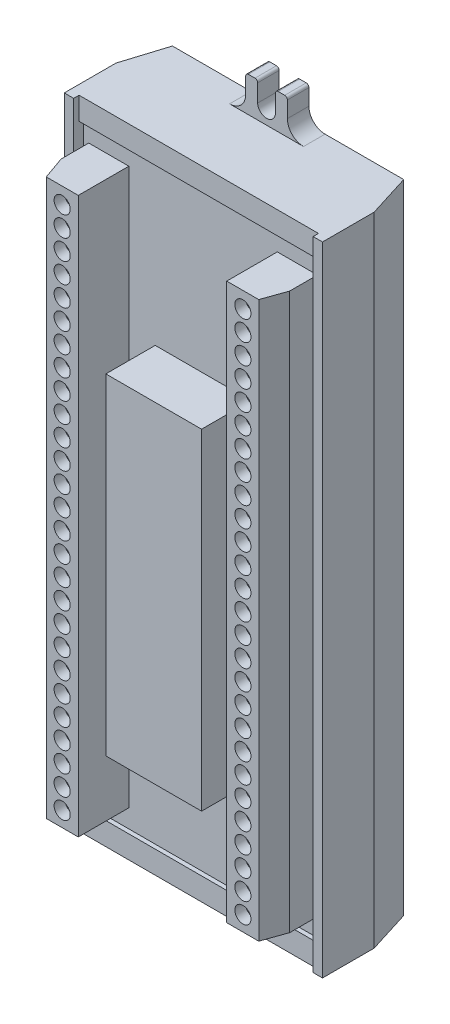
SolidWorks part; units mm, degrees
ref_plane "Front" through (0, 0, 0) normal (0, 0, 1) x (1, 0, 0)
ref_plane "Top" through (0, 0, 0) normal (0, 1, 0) x (1, 0, 0)
ref_plane "Right" through (0, 0, 0) normal (1, 0, 0) x (0, 0, -1)
sketch "Sketch1" plane through (0, 0, 0) normal (0, 1, 0) x (1, 0, 0)
  line L1 (-24, 8.8) -> (24, 8.8)
  line L2 (-24, 8.8) -> (-24, -8.8)
  line L3 (-24, -8.8) -> (24, -8.8)
  line L4 (24, 8.8) -> (24, -8.8)
  line L5 (-24, 8.8) -> (24, -8.8) construction
  line L6 (-24, -8.8) -> (24, 8.8) construction
  point P0 (0, 0)
  dimension "D1" = 48
  dimension "D2" = 17.6
extrude "Boss-Extrude1" add sketch "Sketch1" along normal blind 118.5
sketch "Sketch2" plane through (0, 0, 0) normal (0, -1, 0) x (1, 0, 0)
  line L0 (-24, 8.8) -> (24, 8.8) construction
  line L1 (-22.25, 8.8) -> (22.25, 8.8)
  line L2 (-22.25, 8.8) -> (-22.25, 7.8)
  line L3 (-22.25, 7.8) -> (22.25, 7.8)
  line L4 (22.25, 8.8) -> (22.25, 7.8)
  line L5 (-24, -8.8) -> (-24, 8.8) construction
  line L6 (24, 8.8) -> (24, -8.8) construction
  line L7 (-24, -0.8) -> (-21.5, -8.8)
  line L8 (24, -8.8) -> (-24, -8.8) construction
  line L9 (-21.5, -8.8) -> (-24, -8.8)
  line L10 (-24, -8.8) -> (-24, -0.8)
  line L11 (24, -8.8) -> (21.5, -8.8)
  line L12 (21.5, -8.8) -> (24, -0.8)
  line L13 (24, -0.8) -> (24, -8.8)
  dimension "D1" = 1
  dimension "D2" = 1.75
  dimension "D3" = 1.75
  dimension "D4" = 8
  dimension "D5" = 8
  dimension "D6" = 2.5
  dimension "D7" = 2.5
extrude "Cut-Extrude1" cut sketch "Sketch2" against normal through all
sketch "Sketch3" plane through (0, 0, 7.8) normal (0, 0, 1) x (1, 0, 0)
  line L0 (-22.25, 118.5) -> (-22.25, 0) construction
  line L1 (-22.25, 114.3) -> (22.25, 114.3)
  line L2 (-22.25, 114.3) -> (-22.25, 4.2)
  line L3 (-22.25, 4.2) -> (22.25, 4.2)
  line L4 (22.25, 114.3) -> (22.25, 4.2)
  line L5 (22.25, 118.5) -> (22.25, 0) construction
  line L6 (-22.25, 118.5) -> (22.25, 118.5) construction
  line L7 (-22.25, 0) -> (22.25, 0) construction
  dimension "D1" = 4.2
  dimension "D2" = 4.2
extrude "Cut-Extrude2" cut sketch "Sketch3" against normal blind 0.8
sketch "Sketch4" plane through (0, 0, -8.8) normal (0, 0, -1) x (-1, 0, 0)
  line L0 (0, 148.6078) -> (0, -24.1763) construction
  line L1 (-21.5, 118.5) -> (21.5, 118.5) construction
  line L2 (-3.875, 125) -> (3.875, 125)
  line L3 (-3.875, 125) -> (-3.875, 118.5)
  line L4 (-3.875, 118.5) -> (3.875, 118.5)
  line L5 (3.875, 125) -> (3.875, 118.5)
  line L6 (-3.875, 125) -> (3.875, 118.5) construction
  line L7 (-3.875, 118.5) -> (3.875, 125) construction
  line L8 (-21.5, 0) -> (21.5, 0) construction
  line L9 (3.875, -6.5) -> (-3.875, -6.5)
  line L10 (3.875, -6.5) -> (3.875, 0)
  line L11 (3.875, 0) -> (-3.875, 0)
  line L12 (-3.875, -6.5) -> (-3.875, 0)
  line L13 (3.875, -6.5) -> (-3.875, 0) construction
  line L14 (3.875, 0) -> (-3.875, -6.5) construction
  point P3 (0, 121.75)
  point P10 (0, -3.25)
  dimension "D1" = 6.5
  dimension "D2" = 6.5
  dimension "D3" = 7.75
  dimension "D4" = 7.75
extrude "Boss-Extrude2" add sketch "Sketch4" against normal blind 4
fillet "Fillet1" radius 3 4 edges at (-3.875, 118.5, -6.8) (3.875, 118.5, -6.8) (3.875, 0, -6.8) (-3.875, 0, -6.8)
sketch "Sketch5" plane through (0, 0, -8.8) normal (0, 0, -1) x (-1, 0, 0)
  line L0 (0, 132.5228) -> (0, -15.2026) construction
  line L1 (0, 129.8065) -> (0, 121.25) construction
  line L2 (1.65, 129.8065) -> (1.65, 121.25)
  line L3 (-1.65, 129.8065) -> (-1.65, 121.25)
  line L4 (0, -2.75) -> (0, -10.353) construction
  line L5 (1.65, -2.75) -> (1.65, -10.353)
  line L6 (-1.65, -2.75) -> (-1.65, -10.353)
  line L7 (-24, 59.25) -> (24, 59.25) construction
  line L8 (-24, 118.5) -> (-24, 0) construction
  line L9 (24, 118.5) -> (24, 0) construction
  arc A0 (1.65, 129.8065) -> (-1.65, 129.8065) centre (0, 129.8065) ccw
  arc A1 (-1.65, 121.25) -> (1.65, 121.25) centre (0, 121.25) ccw
  arc A2 (1.65, -2.75) -> (-1.65, -2.75) centre (0, -2.75) ccw
  arc A3 (-1.65, -10.353) -> (1.65, -10.353) centre (0, -10.353) ccw
  point P5 (0, 125.5283)
  point P10 (0, -6.5515)
  point P17 (1.65, 125.5283)
  dimension "D3" = 62
  dimension "D4" = 62
  dimension "D1" = 3.3
  dimension "D2" = 3.3
extrude "Cut-Extrude3" cut sketch "Sketch5" against normal through all
fillet "Fillet2" radius 0.5 8 edges at (3.875, -6.5, -6.8) (1.65, -6.5, -6.8) (-1.65, -6.5, -6.8) (-3.875, -6.5, -6.8) (-3.875, 125, -6.8) (-1.65, 125, -6.8) (1.65, 125, -6.8) (3.875, 125, -6.8)
sketch "Sketch6" plane through (0, 0, 7) normal (0, 0, 1) x (1, 0, 0)
  line L0 (22.25, 114.3) -> (-22.25, 114.3) construction
  line L1 (-21.25, 110.9) -> (-13.8, 110.9)
  line L2 (-21.25, 110.9) -> (-21.25, 7.6)
  line L3 (-21.25, 7.6) -> (-13.8, 7.6)
  line L4 (-13.8, 110.9) -> (-13.8, 7.6)
  line L5 (-22.25, 4.2) -> (22.25, 4.2) construction
  line L6 (-22.25, 114.3) -> (-22.25, 4.2) construction
  line L7 (0, 114.3) -> (0, 0) construction
  line L8 (13.8, 110.9) -> (13.8, 7.6)
  line L9 (21.25, 7.6) -> (13.8, 7.6)
  line L10 (21.25, 110.9) -> (21.25, 7.6)
  line L11 (21.25, 110.9) -> (13.8, 110.9)
  dimension "D1" = 103.3
  dimension "D2" = 7.45
  dimension "D3" = 3.4
  dimension "D4" = 3.4
  dimension "D5" = 1
extrude "Boss-Extrude3" add sketch "Sketch6" along normal blind 9.4
sketch "Sketch7" plane through (0, 7.6, 0) normal (0, -1, 0) x (1, 0, 0)
  line L0 (-19.75, 16.4) -> (-21.25, 12.15)
  line L1 (-21.25, 16.4) -> (-13.8, 16.4) construction
  line L2 (-21.25, 16.4) -> (-21.25, 7) construction
  line L3 (-21.25, 12.15) -> (-21.25, 16.4)
  line L4 (-21.25, 16.4) -> (-19.75, 16.4)
  line L5 (0, 0) -> (0, 20.5716) construction
  line L6 (21.25, 16.4) -> (19.75, 16.4)
  line L7 (21.25, 12.15) -> (21.25, 16.4)
  line L8 (19.75, 16.4) -> (21.25, 12.15)
  dimension "D1" = 4.25
  dimension "D2" = 1.5
extrude "Cut-Extrude4" cut sketch "Sketch7" against normal through all
sketch "Sketch8" plane through (0, 0, 16.4) normal (0, 0, 1) x (1, 0, 0)
  line L0 (-13.8, 7.6) -> (-13.8, 110.9) construction
  line L1 (-13.8, 110.9) -> (-21.25, 110.9) construction
  line L2 (0, 0) -> (0, 144.4934) construction
  circle A0 centre (-16.8, 107.9) radius 1.5
  circle A1 centre (-16.8, 104.15) radius 1.5
  circle A2 centre (-16.8, 100.4) radius 1.5
  circle A3 centre (-16.8, 96.65) radius 1.5
  circle A4 centre (-16.8, 92.9) radius 1.5
  circle A5 centre (-16.8, 89.15) radius 1.5
  circle A6 centre (-16.8, 85.4) radius 1.5
  circle A7 centre (-16.8, 81.65) radius 1.5
  circle A8 centre (-16.8, 77.9) radius 1.5
  circle A9 centre (-16.8, 74.15) radius 1.5
  circle A10 centre (-16.8, 70.4) radius 1.5
  circle A11 centre (-16.8, 66.65) radius 1.5
  circle A12 centre (-16.8, 62.9) radius 1.5
  circle A13 centre (-16.8, 59.15) radius 1.5
  circle A14 centre (-16.8, 55.4) radius 1.5
  circle A15 centre (-16.8, 51.65) radius 1.5
  circle A16 centre (-16.8, 47.9) radius 1.5
  circle A17 centre (-16.8, 44.15) radius 1.5
  circle A18 centre (-16.8, 40.4) radius 1.5
  circle A19 centre (-16.8, 36.65) radius 1.5
  circle A20 centre (-16.8, 32.9) radius 1.5
  circle A21 centre (-16.8, 29.15) radius 1.5
  circle A22 centre (-16.8, 25.4) radius 1.5
  circle A23 centre (-16.8, 21.65) radius 1.5
  circle A24 centre (-16.8, 17.9) radius 1.5
  circle A25 centre (-16.8, 14.15) radius 1.5
  circle A26 centre (-16.8, 10.4) radius 1.5
  circle A27 centre (16.8, 10.4) radius 1.5
  circle A28 centre (16.8, 14.15) radius 1.5
  circle A29 centre (16.8, 17.9) radius 1.5
  circle A30 centre (16.8, 21.65) radius 1.5
  circle A31 centre (16.8, 25.4) radius 1.5
  circle A32 centre (16.8, 29.15) radius 1.5
  circle A33 centre (16.8, 32.9) radius 1.5
  circle A34 centre (16.8, 36.65) radius 1.5
  circle A35 centre (16.8, 40.4) radius 1.5
  circle A36 centre (16.8, 44.15) radius 1.5
  circle A37 centre (16.8, 47.9) radius 1.5
  circle A38 centre (16.8, 51.65) radius 1.5
  circle A39 centre (16.8, 55.4) radius 1.5
  circle A40 centre (16.8, 59.15) radius 1.5
  circle A41 centre (16.8, 62.9) radius 1.5
  circle A42 centre (16.8, 66.65) radius 1.5
  circle A43 centre (16.8, 70.4) radius 1.5
  circle A44 centre (16.8, 74.15) radius 1.5
  circle A45 centre (16.8, 77.9) radius 1.5
  circle A46 centre (16.8, 81.65) radius 1.5
  circle A47 centre (16.8, 85.4) radius 1.5
  circle A48 centre (16.8, 89.15) radius 1.5
  circle A49 centre (16.8, 92.9) radius 1.5
  circle A50 centre (16.8, 96.65) radius 1.5
  circle A51 centre (16.8, 100.4) radius 1.5
  circle A52 centre (16.8, 104.15) radius 1.5
  circle A53 centre (16.8, 107.9) radius 1.5
  dimension "D1" = 3
  dimension "D2" = 3
  dimension "D3" = 3
  dimension "D4" = 27
extrude "Cut-Extrude5" cut sketch "Sketch8" against normal blind 2
sketch "Sketch9" plane through (0, 0, 7) normal (0, 0, 1) x (1, 0, 0)
  line L0 (-22.25, 4.2) -> (22.25, 4.2) construction
  line L1 (-8.8988, 23) -> (8.9012, 23)
  line L2 (-8.8988, 23) -> (-8.8988, 84.5)
  line L3 (-8.8988, 84.5) -> (8.9012, 84.5)
  line L4 (8.9012, 23) -> (8.9012, 84.5)
  line L5 (-8.8988, 23) -> (8.9012, 84.5) construction
  line L6 (-8.8988, 84.5) -> (8.9012, 23) construction
  point P0 (0.0012, 53.75)
  dimension "D1" = 17.8
  dimension "D2" = 61.5
  dimension "D3" = 18.8
extrude "Boss-Extrude4" add sketch "Sketch9" along normal blind 9.18
